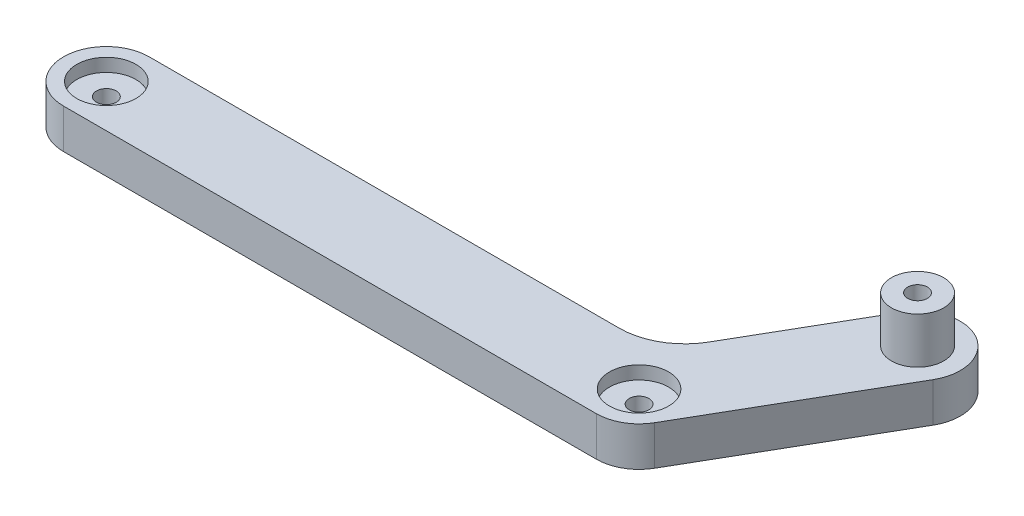
SolidWorks part; units mm, degrees
ref_plane "Front Plane" through (0, 0, 0) normal (0, 0, 1) x (1, 0, 0)
ref_plane "Top Plane" through (0, 0, 0) normal (0, 1, 0) x (1, 0, 0)
ref_plane "Right Plane" through (0, 0, 0) normal (1, 0, 0) x (0, 0, -1)
sketch "Sketch1" plane through (0, 0, 0) normal (0, 1, 0) x (1, 0, 0)
  line L0 (0, 0) -> (81, 0) construction
  line L1 (0, 6.5) -> (71.4737, 6.5)
  line L2 (0, -6.5) -> (81, -6.5)
  line L3 (81, 0) -> (96.5, 26.8468) construction
  line L4 (86.6292, -3.25) -> (102.1292, 23.5968)
  line L5 (80.134, 11.5) -> (90.8708, 30.0968)
  line L6 (75.3708, 3.25) -> (90.8708, 30.0968) construction
  circle A0 centre (0, 0) radius 1.5
  arc A1 (0, 6.5) -> (0, -6.5) centre (0, 0) ccw
  arc A2 (81, -6.5) -> (86.6292, -3.25) centre (81, 0) ccw
  circle A3 centre (81, 0) radius 1.5
  circle A4 centre (0, 0) radius 6.5 construction
  circle A5 centre (96.5, 26.8468) radius 1.5
  arc A6 (102.1292, 23.5968) -> (90.8708, 30.0968) centre (96.5, 26.8468) ccw
  circle A7 centre (96.5, 26.8468) radius 6.5 construction
  arc A8 (80.134, 11.5) -> (71.4737, 6.5) centre (71.4737, 16.5) cw
  dimension "D1" = 3
  dimension "D5" = 3
  dimension "D10" = 10
  dimension "D4" = 81
  dimension "D7" = 60
  dimension "D8" = 31
  dimension "D9" = 6.5
  dimension "D2" = 5
  dimension "D6" = 5
  dimension "D3" = 2
extrude "Boss-Extrude1" add sketch "Sketch1" along normal blind 6
sketch "Sketch2" plane through (0, 6, 0) normal (0, 1, 0) x (1, 0, 0)
  circle A5 centre (0, 0) radius 4.5
  circle A6 centre (0, 0) radius 4.5
  circle A8 centre (81, 0) radius 4.5
  circle A9 centre (81, 0) radius 4.5
  dimension "D1" = 3
  dimension "D2" = 3
extrude "Cut-Extrude1" cut sketch "Sketch2" against normal blind 2
sketch "Sketch3" plane through (0, 6, 0) normal (0, 1, 0) x (1, 0, 0)
  circle A0 centre (96.5, 26.8468) radius 3.975
  arc A1 (102.1292, 23.5968) -> (90.8708, 30.0968) centre (96.5, 26.8468) ccw construction
  circle A2 centre (96.5, 26.8468) radius 1.5 construction
  circle A3 centre (96.5, 26.8468) radius 1.5
  dimension "D1" = 7.95
extrude "Boss-Extrude2" add sketch "Sketch3" along normal blind 7
